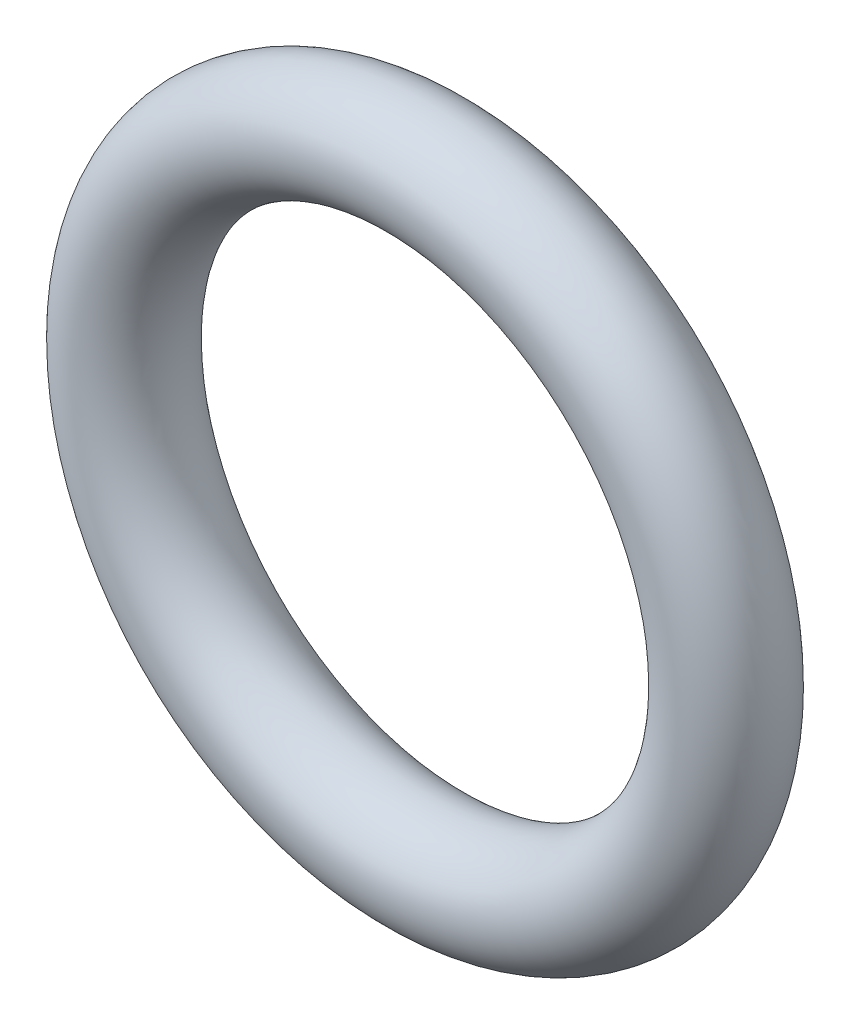
SolidWorks part; units mm, degrees
material "Бутил"
ref_plane "Спереди" through (0, 0, 0) normal (0, 0, 1) x (1, 0, 0)
ref_plane "Сверху" through (0, 0, 0) normal (0, 1, 0) x (1, 0, 0)
ref_plane "Справа" through (0, 0, 0) normal (1, 0, 0) x (0, 0, -1)
sketch "Эскиз1" plane through (0, 0, 0) normal (0, 1, 0) x (1, 0, 0)
  line L0 (0, 0) -> (0, 4.4138) construction
  circle A0 centre (-8.25, 1.5) radius 1.5
  dimension "D2" = 3
  dimension "D3" = 1.5
  dimension "D1" = 16.5
revolve "Повернуть1" add sketch "Эскиз1" angle 360 about L0
ref_plane "Плоскость1" through (0, 0, 0) normal (0, 0, 1) x (1, 0, 0)
